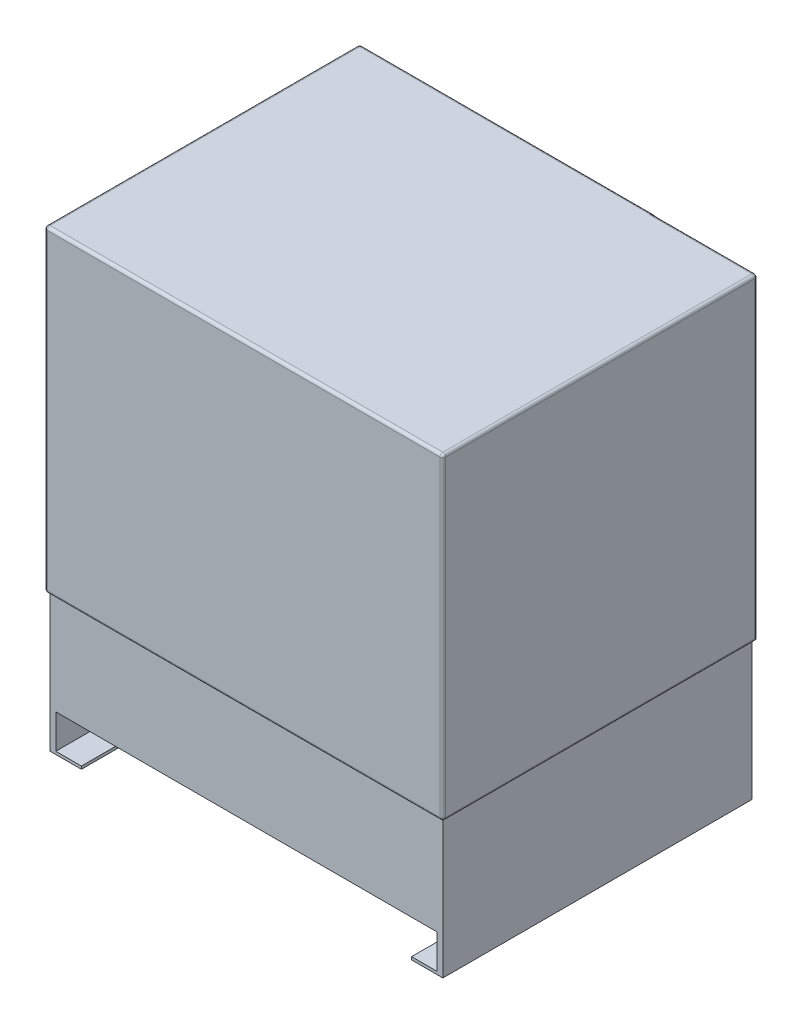
SolidWorks part; units mm, degrees
ref_plane "Front Plane" through (0, 0, 0) normal (0, 0, 1) x (1, 0, 0)
ref_plane "Horiz Plane" through (0, 0, 0) normal (0, 1, 0) x (1, 0, 0)
ref_plane "Right Plane" through (0, 0, 0) normal (1, 0, 0) x (0, 0, -1)
sketch "草图1" plane through (0, 0, 0) normal (0, 0, 1) x (1, 0, 0)
  line L1 (350, -400) -> (-350, -400)
  line L2 (350, -400) -> (350, 400)
  line L3 (350, 400) -> (-350, 400)
  line L4 (-350, -400) -> (-350, 400)
  line L5 (350, -400) -> (-350, 400) construction
  line L6 (350, 400) -> (-350, -400) construction
  point P0 (0, 0)
  dimension "D1" = 700
  dimension "D2" = 800
extrude "凸台-拉伸1" add sketch "草图1" along normal mid plane 554
sketch "草图2" plane through (0, 0, -277) normal (0, 0, -1) x (-1, 0, 0)
  line L0 (-350, -400) -> (-350, 400) construction
  line L2 (290, -395) -> (290, -400)
  line L3 (335, -395) -> (290, -395)
  line L4 (-280, -335) -> (-335, -335)
  line L5 (-335, -335) -> (-335, -395)
  line L6 (-335, -395) -> (-290, -395)
  line L7 (-290, -395) -> (-290, -400)
  line L8 (350, -400) -> (-350, -400) construction
  line L9 (335, -335) -> (335, -395)
  line L10 (0, 0) -> (0, -400) construction
  line L11 (280, -335) -> (335, -335)
  line L12 (-290, -400) -> (290, -400)
  line L13 (280, -335) -> (-280, -335)
  line L14 (-280, -335) -> (-329.633, -434.851)
  dimension "D1" = 65
  dimension "D2" = 5
  dimension "D3" = 55
  dimension "D4" = 15
  dimension "D5" = 60
extrude "切除-拉伸1" cut sketch "草图2" against normal through all contours L4 L5 L6 L7 L12 L2 L3 L9 L11 L13
sketch "草图3" plane through (0, 0, 277) normal (0, 0, 1) x (1, 0, 0)
  line L0 (-350, 400) -> (-350, -400) construction
  line L1 (-350, -158) -> (350, -158)
  line L2 (-350, -158) -> (-350, -160)
  line L3 (-350, -160) -> (350, -160)
  line L4 (350, -158) -> (350, -160)
  line L5 (350, -400) -> (350, 400) construction
  line L6 (-350, -400) -> (-290, -400) construction
  dimension "D1" = 240
  dimension "D2" = 2
extrude "切除-拉伸2" cut sketch "草图3" against normal through all
sketch "草图4" plane through (0, 0, -277) normal (0, 0, -1) x (-1, 0, 0)
  line L1 (350, -400) -> (-350, -400)
  line L2 (350, -400) -> (350, -160)
  line L3 (350, -160) -> (-350, -160)
  line L4 (-350, -400) -> (-350, -160)
extrude "切除-拉伸3" cut sketch "草图4" against normal blind 5
sketch "草图6" plane through (0, 0, 277) normal (0, 0, 1) x (1, 0, 0)
  line L1 (350, -400) -> (-350, -400)
  line L2 (350, -400) -> (350, -160)
  line L3 (350, -160) -> (-350, -160)
  line L4 (-350, -400) -> (-350, -160)
extrude "切除-拉伸5" cut sketch "草图6" against normal blind 5
sketch "草图7" plane through (-350, 0, 0) normal (-1, 0, 0) x (0, 0, 1)
  line L1 (272, -400) -> (-272, -400)
  line L2 (272, -400) -> (272, -160)
  line L3 (272, -160) -> (-272, -160)
  line L4 (-272, -400) -> (-272, -160)
extrude "切除-拉伸6" cut sketch "草图7" against normal blind 5
sketch "草图8" plane through (350, 0, 0) normal (1, 0, 0) x (0, 0, -1)
  line L1 (272, -400) -> (-272, -400)
  line L2 (272, -400) -> (272, -160)
  line L3 (272, -160) -> (-272, -160)
  line L4 (-272, -400) -> (-272, -160)
extrude "切除-拉伸7" cut sketch "草图8" against normal blind 5
sketch "草图9" plane through (0, 0, -272) normal (0, 0, -1) x (-1, 0, 0)
  line L1 (-335, -335) -> (335, -335)
  line L2 (-335, -335) -> (-335, -395)
  line L3 (-335, -395) -> (335, -395)
  line L4 (335, -335) -> (335, -395)
extrude "凸台-拉伸2" add sketch "草图9" against normal blind 5
sketch "草图11" plane through (0, 0, -277) normal (0, 0, -1) x (-1, 0, 0)
  line L0 (-345, -400) -> (-290, -400) construction
  line L1 (-350, 400) -> (-170, 400)
  line L2 (-350, 400) -> (-350, -400)
  line L3 (-350, -400) -> (-170, -400)
  line L4 (-170, 400) -> (-170, -400)
  dimension "D1" = 180
extrude "切除-拉伸8" cut sketch "草图11" against normal blind 1
sketch "草图12" plane through (0, 0, -272) normal (0, 0, -1) x (-1, 0, 0)
  line L0 (-170, -158) -> (-170, 400) construction
  line L1 (-345, -160) -> (-170, -160)
  line L2 (-345, -160) -> (-345, -400)
  line L3 (-345, -400) -> (-170, -400)
  line L4 (-170, -160) -> (-170, -400)
  line L6 (-345, -400) -> (-290, -400) construction
extrude "切除-拉伸9" cut sketch "草图12" against normal blind 1
fillet "圆角3" radius 5 13 edges at (0, -158, 277) (-350, 121, 277) (-350, -158, 0) (-350, 121, -277) (350, -158, 0.5) (350, 121, 277) (350, 121, -276) (350, 400, 0.5) (0, 400, 277) (-350, 400, 0) (-90, 400, -277) (170, 400, -276.5) (260, 400, -276)
sketch "草图13" plane through (0, 0, -276) normal (0, 0, -1) x (-1, 0, 0)
  text T0 "<r90>0</r>\r\n<r90>0</r>\r\n<r90>2</r>\r\n<r90>X</r>\r\n<r90>D</r>" font "Century Gothic" height 30
sketch "草图14" plane through (0, 0, -277) normal (0, 0, -1) x (-1, 0, 0)
  text T0 "YASKAWA" font "Century Gothic" height 30
extrude "凸台-拉伸4" add sketch "草图14" along normal blind 2
sketch "草图15" plane through (0, 0, -272) normal (0, 0, -1) x (-1, 0, 0)
  line L0 (290, -400) -> (290, -395)
  line L1 (290, -395) -> (335, -395)
  line L2 (335, -395) -> (335, -335)
  line L3 (335, -335) -> (-335, -335)
  line L4 (-335, -335) -> (-335, -395)
  line L5 (-335, -395) -> (-290, -395)
  line L6 (-290, -395) -> (-290, -400)
  line L7 (-290, -400) -> (290, -400)
extrude "切除-拉伸10" cut sketch "草图15" against normal through all
extrude "凸台-拉伸5" add sketch "草图13" along normal blind 2
